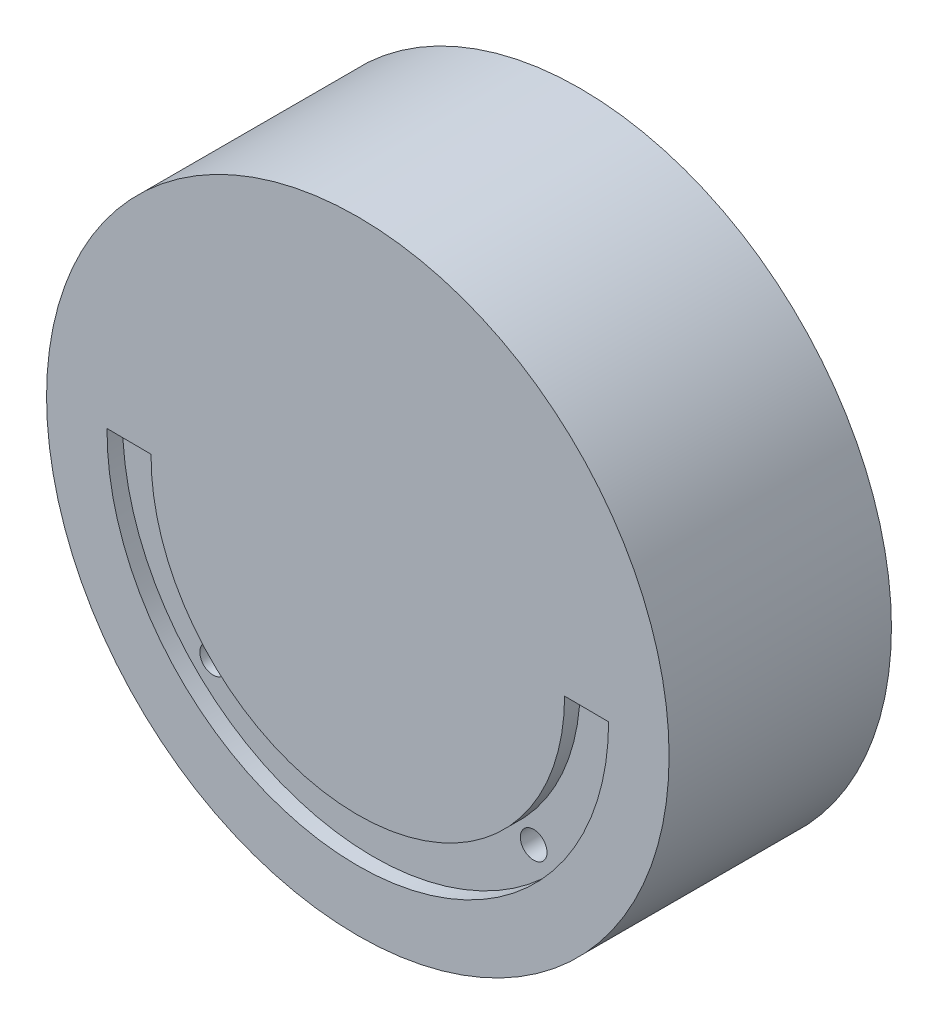
SolidWorks part; units mm, degrees
ref_plane "정면" through (0, 0, 0) normal (0, 0, 1) x (1, 0, 0)
ref_plane "윗면" through (0, 0, 0) normal (0, 1, 0) x (1, 0, 0)
ref_plane "우측면" through (0, 0, 0) normal (1, 0, 0) x (0, 0, -1)
sketch "스케치1" plane through (0, 0, 0) normal (0, 0, 1) x (1, 0, 0)
  circle A0 centre (0, 0) radius 70
  dimension "D1" = 140
extrude "보스-돌출1" add sketch "스케치1" along normal blind 50
sketch "스케치3" plane through (0, 0, 50) normal (0, 0, 1) x (1, 0, 0)
  line L0 (-56.3972, 0.5645) -> (-46.4973, 0.5005)
  line L1 (46.4999, -0.1005) -> (56.3998, -0.1645)
  arc A0 (-56.3972, 0.5645) -> (56.3998, -0.1645) centre (0, 0) ccw
  arc A1 (-46.4973, 0.5005) -> (46.4999, -0.1005) centre (0, 0) ccw
  dimension "D1" = 112.8
  dimension "D2" = 93
  dimension "D3" = 0.2
extrude "컷-돌출1" cut sketch "스케치3" against normal blind 3.5
sketch "스케치4" plane through (0, 0, 46.5) normal (0, 0, 1) x (1, 0, 0)
  line L0 (0, 0) -> (0, -54.6732) construction
  line L1 (0, 0) -> (-36.0401, -36.0401) construction
  circle A0 centre (-36.0401, -36.0401) radius 3
  circle A1 centre (36.0401, -36.0401) radius 3
  circle A2 centre (0, 0) radius 50.9684 construction
  dimension "D1" = 6
  dimension "D2" = 45
extrude "컷-돌출2" cut sketch "스케치4" against normal blind 6
